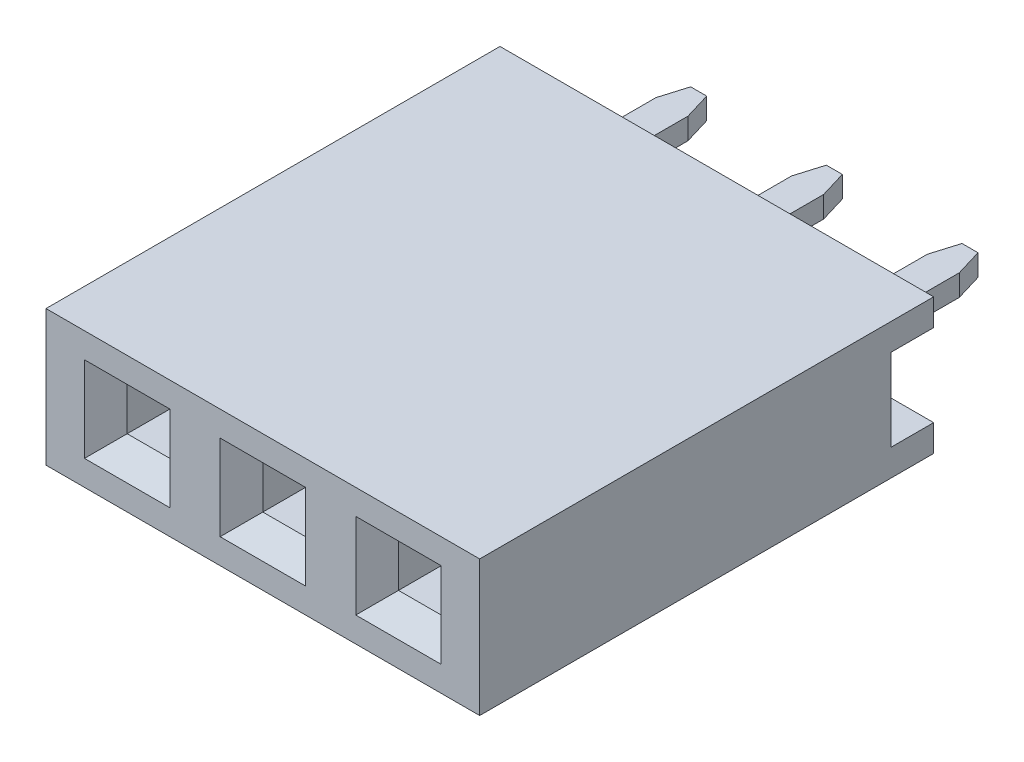
SolidWorks part; units mm, degrees
ref_plane "Front Plane" through (0, 0, 0) normal (0, 0, 1) x (1, 0, 0)
ref_plane "Top Plane" through (0, 0, 0) normal (0, 1, 0) x (1, 0, 0)
ref_plane "Right Plane" through (0, 0, 0) normal (1, 0, 0) x (0, 0, -1)
sketch "Sketch1" plane through (0, 0, 0) normal (1, 0, 0) x (0, -1, 0)
  line L0 (0, 0) -> (0, -8.5) construction
  line L1 (-1.27, 0) -> (1.27, 0)
  line L2 (-1.27, 0) -> (-1.27, -8.5)
  line L3 (-1.27, -8.5) -> (1.27, -8.5)
  line L4 (1.27, 0) -> (1.27, -8.5)
  point P0 (0, 0)
  dimension "D1" = 2.54
  dimension "D2" = 8.5
extrude "Boss-Extrude1" add sketch "Sketch1" along normal mid plane 3.04
sketch "Эскиз1" plane through (1.52, 0, 0) normal (1, 0, 0) x (0, 0, -1)
  line L0 (0, -0.77) -> (-0.8, -0.77)
  line L1 (0, -1.27) -> (0, 1.27) construction
  line L2 (-0.8, -0.77) -> (-0.8, 0.77)
  line L4 (-0.8, 0.77) -> (0, 0.77)
  line L5 (0, 0.77) -> (0, -0.77)
  line L6 (-8.5, -1.27) -> (0, -1.27) construction
  dimension "D1" = 0.5
  dimension "D2" = 0.8
  dimension "D3" = 0.5
extrude "Вырез-Вытянуть1" cut sketch "Эскиз1" against normal through all
sketch "Sketch2" plane through (0, 0, 8.5) normal (0, 0, 1) x (-1, 0, 0)
  line L0 (0, -1.27) -> (0, 1.27) construction
  line L3 (-1.52, -1.27) -> (1.52, -1.27) construction
  line L4 (-0.4, 0.4) -> (0.4, 0.4)
  line L5 (-0.4, 0.4) -> (-0.4, -0.4)
  line L6 (-0.4, -0.4) -> (0.4, -0.4)
  line L7 (0.4, 0.4) -> (0.4, -0.4)
  line L8 (-0.4, 0.4) -> (0.4, -0.4) construction
  line L9 (-0.4, -0.4) -> (0.4, 0.4) construction
  line L10 (-1.52, 1.27) -> (1.52, 1.27) construction
  point P5 (0, 0)
  dimension "D1" = 0.8
extrude "Cut-Extrude1" cut sketch "Sketch2" against normal offset from surface (7 mm away) 0.7 up to face at (0, 0, 0.8)
chamfer "Фаска1" distance 0.4 angle 45 4 edges at (0, -0.4, 8.5) (0.4, 0, 8.5) (0, 0.4, 8.5) (-0.4, 0, 8.5)
sketch "Sketch3" plane through (0, 0, 0) normal (0, 1, 0) x (1, 0, 0)
  line L0 (-0.3, 0) -> (-0.3, 1.7)
  line L1 (0.3, 0) -> (0.3, -0.8)
  line L2 (-0.3, 1.7) -> (-0.15, 2.2)
  line L3 (-0.15, 2.2) -> (0.15, 2.2)
  line L4 (0, 2.2) -> (0, 0) construction
  line L5 (-0.3, 0) -> (0.3, 0) construction
  line L6 (0.3, 1.7) -> (0.15, 2.2)
  line L7 (0.3, 0) -> (0.3, 1.7)
  line L8 (0.3, -0.8) -> (-0.3, -0.8)
  line L9 (-0.3, -0.8) -> (-0.3, 0)
  line L10 (-1.52, -0.8) -> (1.52, -0.8) construction
  line L11 (0.3, 1.7) -> (-0.3, 1.7) construction
  line L12 (0.4, -1.5) -> (-0.4, -1.5)
  line L13 (-0.4, -1.5) -> (-0.4, -6.9)
  line L14 (-0.4, -6.9) -> (-0.3, -6.9)
  line L15 (-0.3, -6.9) -> (-0.3, -1.6)
  line L16 (-0.3, -1.6) -> (0.3, -1.6)
  line L17 (0.3, -1.6) -> (0.3, -6.9)
  line L18 (0.3, -6.9) -> (0.4, -6.9)
  line L19 (0.4, -6.9) -> (0.4, -1.5)
  line L20 (-0.4, -1.5) -> (-0.4, -8.1) construction
  line L21 (0.4, -1.5) -> (0.4, -8.1) construction
  line L22 (0.4, -1.5) -> (-0.4, -1.5) construction
  dimension "D1" = 0.6
  dimension "D2" = 0.3
  dimension "D3" = 2.2
  dimension "D4" = 0.5
  dimension "D5" = 1.6
  dimension "D6" = 0.1
  dimension "D7" = 0.1
extrude "Boss-Extrude2" add sketch "Sketch3" along normal mid plane 0.4
pattern_linear "LPattern1" count 3 spacing 2.54 along (1, 0, 0) of bodies 103
combine bodies "Соединить1" operation type add bodies to combine 107 104 103
